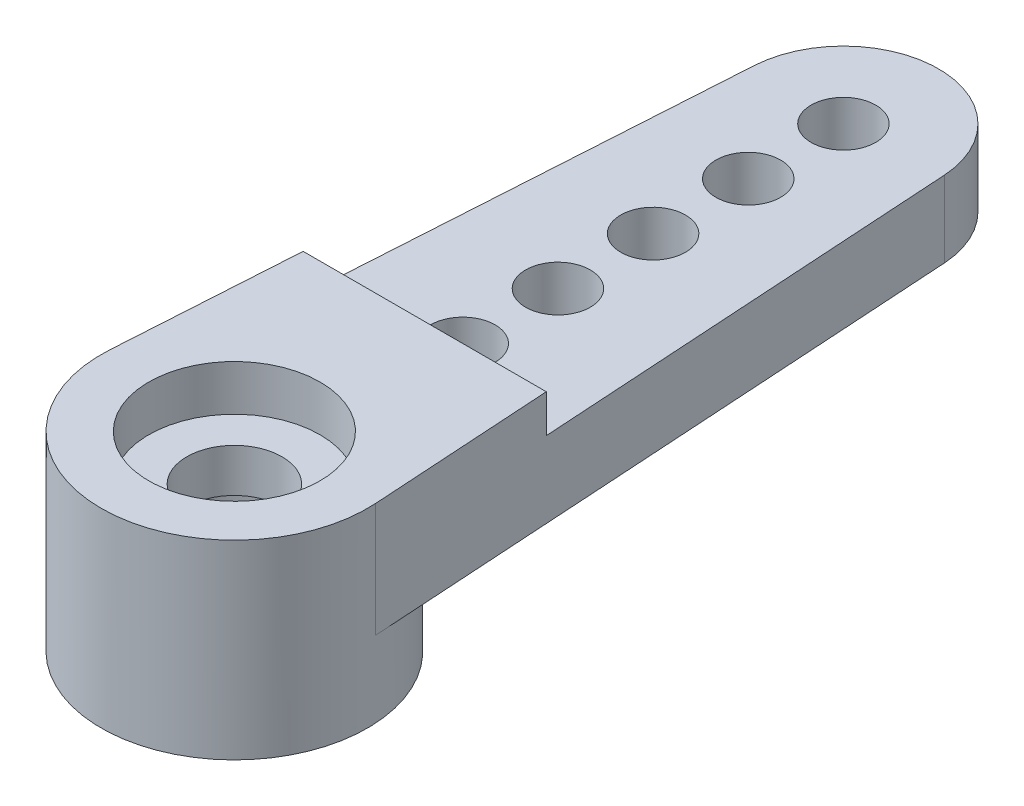
SolidWorks part; units mm, degrees
ref_plane "前视基准面" through (0, 0, 0) normal (0, 0, 1) x (1, 0, 0)
ref_plane "上视基准面" through (0, 0, 0) normal (0, 1, 0) x (1, 0, 0)
ref_plane "右视基准面" through (0, 0, 0) normal (1, 0, 0) x (0, 0, -1)
other "Configuration Table"
sketch "草图1" plane through (0, 0, 0) normal (0, 0, 1) x (1, 0, 0)
  line L0 (0, 0) -> (0, 48.7698) construction
  line L1 (-2.4, 0) -> (-3.5, 0)
  line L2 (-3.5, 0) -> (-3.5, 5)
  line L3 (-3.5, 5) -> (-2.25, 5)
  line L4 (-2.25, 5) -> (-2.25, 3.8)
  line L5 (-2.25, 3.8) -> (-1.25, 3.8)
  line L6 (-1.25, 3.8) -> (-1.25, 2.66)
  line L7 (-1.25, 2.66) -> (-2.4, 2.66)
  line L8 (-2.4, 2.66) -> (-2.4, 0)
  dimension "D1" = 5
  dimension "D2" = 3.5
  dimension "D3" = 2.66
  dimension "D4" = 1.2
  dimension "D5" = 4.5
  dimension "D6" = 4.8
  dimension "D7" = 2.5
revolve "旋转1" add sketch "草图1" angle 360 about L0
ref_plane "基准面1" through (0, 2, 0) normal (0, -1, 0) x (-1, 0, 0)
sketch "草图2" plane through (0, 2, 0) normal (0, -1, 0) x (-1, 0, 0)
  line L0 (-2.4951, 16.1562) -> (-3.4932, 0.2187)
  line L1 (2.4951, 16.1562) -> (3.4932, 0.2187)
  arc A0 (2.4951, 16.1562) -> (-2.4951, 16.1562) centre (0, 16) ccw
  circle A1 centre (0, 0) radius 3.5 construction
  arc A2 (3.4932, 0.2187) -> (-3.4932, 0.2187) centre (0, 0) ccw
  dimension "D1" = 16
  dimension "D2" = 5
extrude "凸台-拉伸1" add sketch "草图2" against normal blind 2
sketch "草图3" plane through (0, 5, 0) normal (0, 1, 0) x (1, 0, 0)
  line L0 (-3.1937, 5) -> (3.1937, 5)
  line L1 (-3.4932, 0.2187) -> (-2.4951, 16.1562) construction
  line L2 (2.4951, 16.1562) -> (3.4932, 0.2187) construction
  line L3 (3.1937, 5) -> (3.4932, 0.2187)
  line L4 (-3.4932, 0.2187) -> (-3.1937, 5)
  arc A0 (3.4932, 0.2187) -> (-3.4932, 0.2187) centre (0, 0) ccw construction
  arc A1 (3.4932, 0.2187) -> (-3.4932, 0.2187) centre (0, 0) ccw
  dimension "D1" = 5
extrude "凸台-拉伸2" add sketch "草图3" against normal blind 1
sketch "草图4" plane through (0, 2, 0) normal (0, -1, 0) x (1, 0, 0)
  circle A0 centre (0, -6) radius 0.85
  circle A1 centre (0, -16) radius 0.85
  circle A2 centre (0, -13.5) radius 0.85
  circle A3 centre (0, -8.5) radius 0.85
  circle A4 centre (0, -11) radius 0.85
  dimension "D1" = 6
  dimension "D2" = 1.7
  dimension "D3" = 2.5
  dimension "D4" = 2.5
  dimension "D5" = 2.5
extrude "切除-拉伸1" cut sketch "草图4" against normal blind 10
